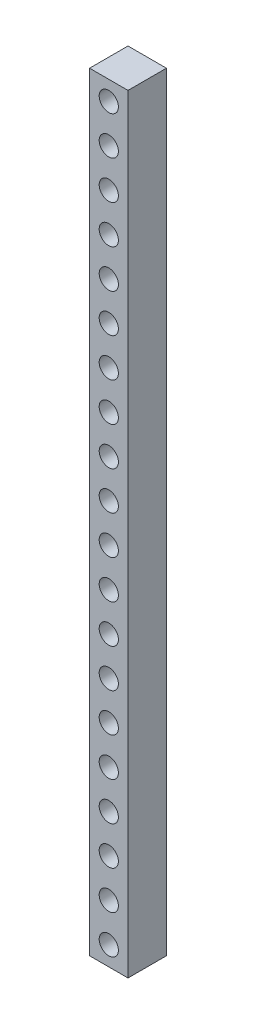
SolidWorks part; units mm, degrees
ref_plane "Plan de face" through (0, 0, 0) normal (0, 0, 1) x (1, 0, 0)
ref_plane "Plan de dessus" through (0, 0, 0) normal (0, 1, 0) x (1, 0, 0)
ref_plane "Plan de droite" through (0, 0, 0) normal (1, 0, 0) x (0, 0, -1)
sketch "Esquisse1" plane through (0, 0, 0) normal (0, 0, 1) x (1, 0, 0)
  line L0 (0, 100) -> (0, 92.8586) construction
  line L1 (5, 100) -> (-5, 100)
  line L2 (5, 100) -> (5, -100)
  line L3 (5, -100) -> (-5, -100)
  line L4 (-5, 100) -> (-5, -100)
  line L5 (5, 100) -> (-5, -100) construction
  line L6 (5, -100) -> (-5, 100) construction
  circle A0 centre (0, 95) radius 2.5
  circle A1 centre (0, 85) radius 2.5
  circle A2 centre (0, 75) radius 2.5
  circle A3 centre (0, 65) radius 2.5
  circle A4 centre (0, 55) radius 2.5
  circle A5 centre (0, 45) radius 2.5
  circle A6 centre (0, 35) radius 2.5
  circle A7 centre (0, 25) radius 2.5
  circle A8 centre (0, 15) radius 2.5
  circle A9 centre (0, 5) radius 2.5
  circle A10 centre (0, -5) radius 2.5
  circle A11 centre (0, -15) radius 2.5
  circle A12 centre (0, -25) radius 2.5
  circle A13 centre (0, -35) radius 2.5
  circle A14 centre (0, -45) radius 2.5
  circle A15 centre (0, -55) radius 2.5
  circle A16 centre (0, -65) radius 2.5
  circle A17 centre (0, -75) radius 2.5
  circle A18 centre (0, -85) radius 2.5
  circle A19 centre (0, -95) radius 2.5
  point P0 (0, 0)
  dimension "D4" = 5
  dimension "D1" = 200
  dimension "D2" = 10
  dimension "D3" = 5
  dimension "D5" = 20
extrude "BASE" add sketch "Esquisse1" along normal blind 10
